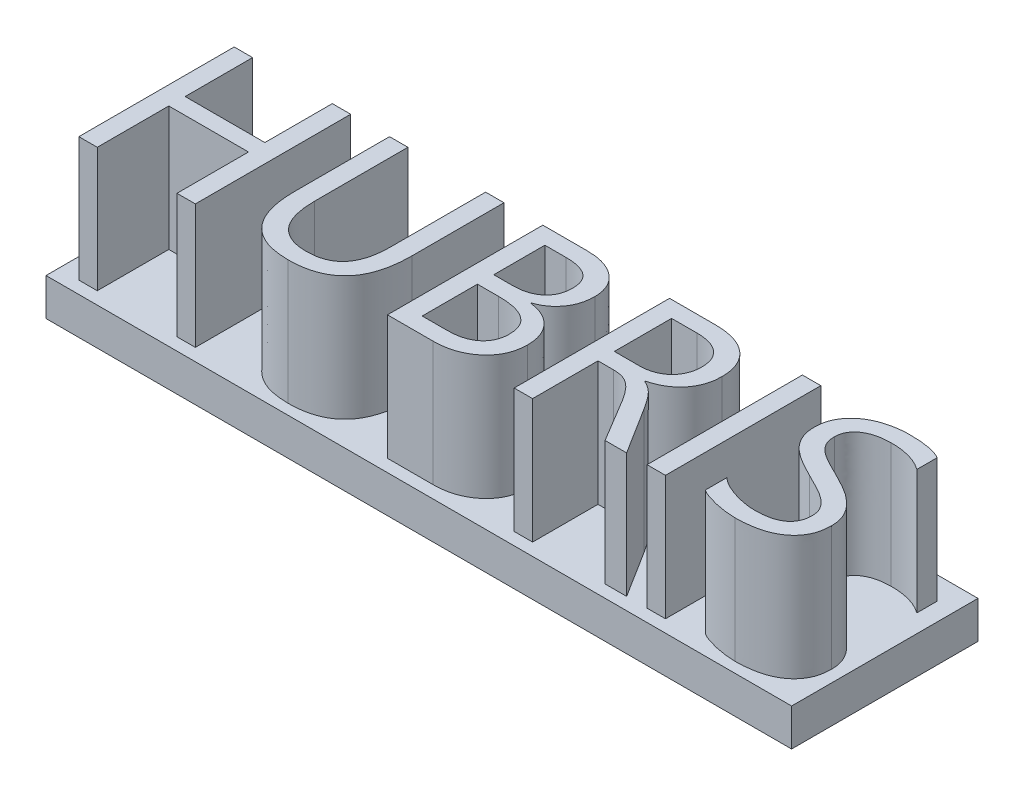
SolidWorks part; units mm, degrees
ref_plane "Front Plane" through (0, 0, 0) normal (0, 0, 1) x (1, 0, 0)
ref_plane "Top Plane" through (0, 0, 0) normal (0, 1, 0) x (1, 0, 0)
ref_plane "Right Plane" through (0, 0, 0) normal (1, 0, 0) x (0, 0, -1)
sketch "Sketch1" plane through (0, 0, 0) normal (0, 1, 0) x (1, 0, 0)
  line L1 (-30, -7.5) -> (30, -7.5)
  line L2 (-30, -7.5) -> (-30, 7.5)
  line L3 (-30, 7.5) -> (30, 7.5)
  line L4 (30, -7.5) -> (30, 7.5)
  line L5 (-30, -7.5) -> (30, 7.5) construction
  line L6 (-30, 7.5) -> (30, -7.5) construction
  point P0 (0, 0)
  dimension "D1" = 15
  dimension "D2" = 60
extrude "Boss-Extrude1" add sketch "Sketch1" along normal blind 10
sketch "Sketch2" plane through (0, 10, 0) normal (0, 1, 0) x (1, 0, 0)
  line L0 (-30, -6.5) -> (30, -6.5) construction
  line L4 (30, -7.5) -> (30, 7.5)
  line L5 (30, 7.5) -> (-30, 7.5)
  line L6 (-30, 7.5) -> (-30, -7.5)
  line L7 (-30, -7.5) -> (30, -7.5)
  line L8 (30, -7.5) -> (30, 7.5) construction
  line L9 (30, 7.5) -> (-30, 7.5) construction
  line L10 (-30, 7.5) -> (-30, -7.5) construction
  line L11 (-30, -7.5) -> (30, -7.5) construction
  text T0 "HUBRIS" font "Segoe UI" height 12.5
  dimension "D2" = 1
  dimension "D1" = 0
extrude "Boss-Extrude2" add sketch "Sketch2" along normal blind 10
sketch "Sketch3" plane through (0, 0, 0) normal (0, -1, 0) x (1, 0, 0)
  line L4 (30, -7.5) -> (30, 7.5)
  line L5 (30, 7.5) -> (-30, 7.5)
  line L6 (-30, 7.5) -> (-30, -7.5)
  line L7 (-30, -7.5) -> (30, -7.5)
  line L8 (30, -7.5) -> (30, 7.5)
  line L9 (30, 7.5) -> (-30, 7.5)
  line L10 (-30, 7.5) -> (-30, -7.5)
  line L11 (-30, -7.5) -> (30, -7.5)
  dimension "D1" = 0
extrude "Cut-Extrude1" cut sketch "Sketch3" against normal blind 7
